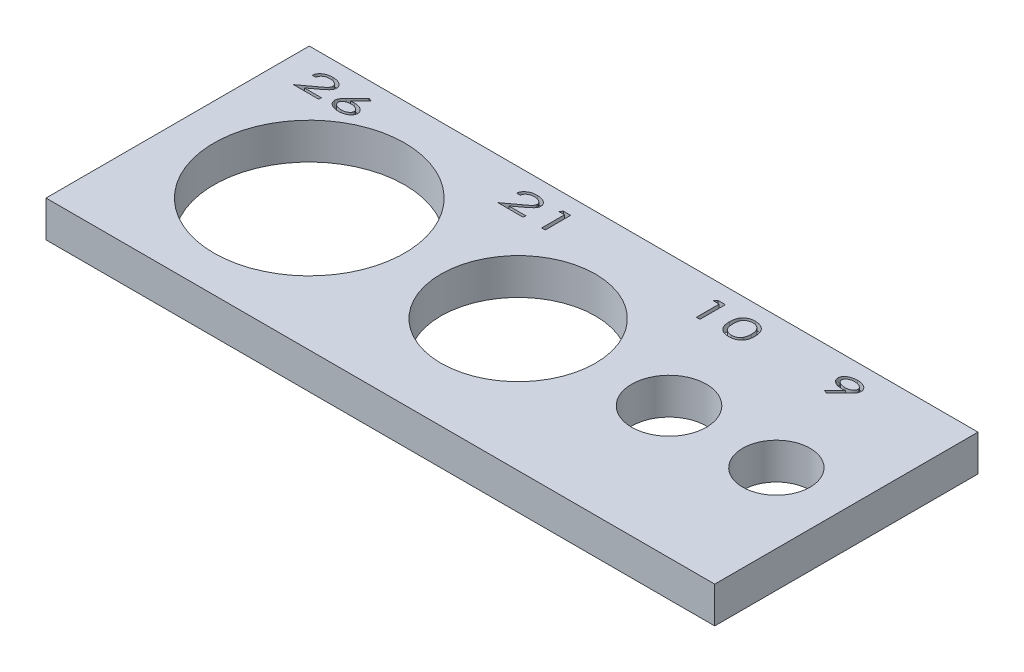
SolidWorks part; units mm, degrees
ref_plane "Спереди" through (0, 0, 0) normal (0, 0, 1) x (1, 0, 0)
ref_plane "Сверху" through (0, 0, 0) normal (0, 1, 0) x (1, 0, 0)
ref_plane "Справа" through (0, 0, 0) normal (1, 0, 0) x (0, 0, -1)
sketch "Эскиз1" plane through (0, 0, 0) normal (0, 1, 0) x (1, 0, 0)
  line L0 (0, 0) -> (5, 0) construction
  line L1 (31.3, 0) -> (36.3, 0) construction
  line L2 (57.6, 0) -> (62.6, 0) construction
  line L3 (72.9, 0) -> (77.9, 0) construction
  line L4 (87.2, 0) -> (92.2, 0) construction
  line L5 (18.15, 13.15) -> (18.15, 18.15) construction
  line L6 (18.15, -13.15) -> (18.15, -18.15) construction
  line L7 (0, 0) -> (0, 18.15)
  line L8 (0, 18.15) -> (92.2, 18.15)
  line L9 (92.2, 18.15) -> (92.2, -18.15)
  line L10 (92.2, -18.15) -> (0, -18.15)
  line L11 (0, -18.15) -> (0, 0)
  circle A0 centre (18.15, 0) radius 13.15
  circle A1 centre (46.95, 0) radius 10.65
  circle A2 centre (67.75, 0) radius 5.15
  circle A3 centre (82.55, 0) radius 4.65
  dimension "D1" = 26.3
  dimension "D2" = 21.3
  dimension "D3" = 10.3
  dimension "D4" = 9.3
  dimension "D5" = 5
extrude "Бобышка-Вытянуть1" add sketch "Эскиз1" along normal blind 5
sketch "Эскиз2" plane through (0, 5, 0) normal (0, 1, 0) x (1, 0, 0)
  text T0 "26        21       10    9" font "Century Gothic" height 3.5
extrude "Вырез-Вытянуть1" cut sketch "Эскиз2" against normal blind 1
